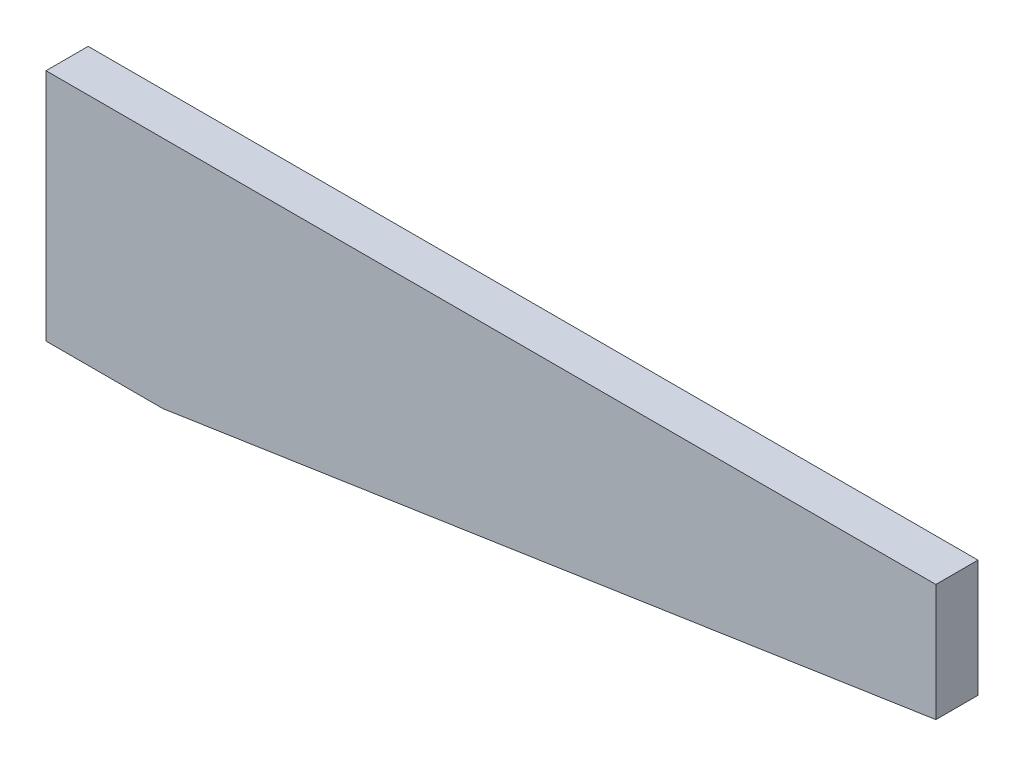
SolidWorks part; units mm, degrees
ref_plane "Front" through (0, 0, 0) normal (0, 0, 1) x (1, 0, 0)
ref_plane "Top" through (0, 0, 0) normal (0, 1, 0) x (1, 0, 0)
ref_plane "Right" through (0, 0, 0) normal (1, 0, 0) x (0, 0, -1)
sketch "Esquisse1" plane through (0, 0, 0) normal (0, 0, 1) x (1, 0, 0)
  line L1 (0, 0) -> (570, 0)
  line L2 (0, 0) -> (0, 150)
  line L3 (0, 150) -> (570, 150)
  line L4 (570, 0) -> (570, 150)
  dimension "D1" = 150
  dimension "D2" = 570
extrude "Boss.-Extru.1" add sketch "Esquisse1" along normal blind 27
sketch "Esquisse2" plane through (0, 0, 27) normal (0, 0, 1) x (1, 0, 0)
  line L0 (75, 0) -> (570, 75)
  line L1 (0, 0) -> (570, 0) construction
  line L2 (570, 0) -> (570, 150) construction
  line L3 (570, 75) -> (570, 0)
  line L4 (570, 0) -> (75, 0)
  line L5 (570, 150) -> (0, 150) construction
  dimension "D1" = 75
  dimension "D2" = 75
extrude "Enlèv. mat.-Extru.1" cut sketch "Esquisse2" against normal through all both and the other way through all
